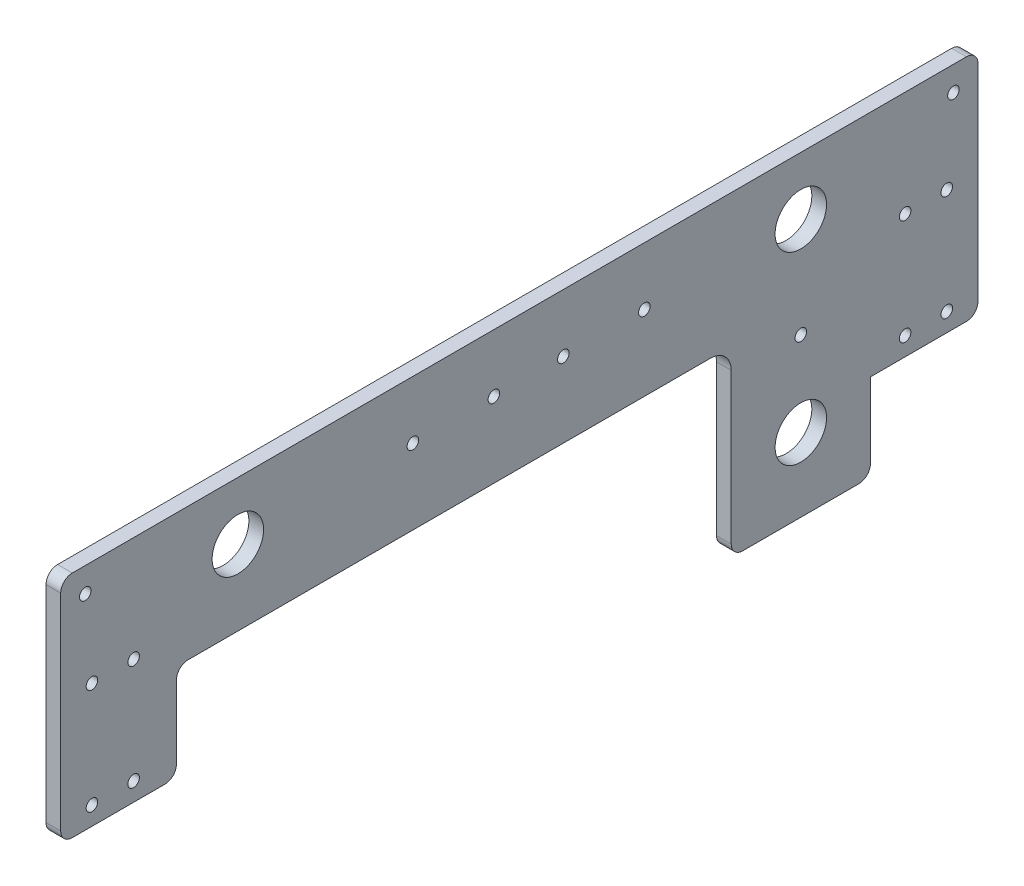
SolidWorks part; units mm, degrees
material "6061-O (SS)"
ref_plane "Alzado" through (0, 0, 0) normal (0, 0, 1) x (1, 0, 0)
ref_plane "Planta" through (0, 0, 0) normal (0, 1, 0) x (1, 0, 0)
ref_plane "Vista lateral" through (0, 0, 0) normal (1, 0, 0) x (0, 0, -1)
sketch "Croquis1" plane through (0, 0, 0) normal (1, 0, 0) x (0, 0, -1)
  line L4 (-30.06, -68.26) -> (-30.06, 1.76)
  line L5 (0, 43.26) -> (0, -68.26) construction
  line L6 (0, 43.26) -> (-243.18, 43.26) construction
  line L7 (30.06, 68.26) -> (-319.71, 68.26) construction
  line L9 (30.06, 10.76) -> (-319.71, 10.76) construction
  line L12 (21.06, 68.26) -> (-319.71, 68.26)
  line L14 (-243.18, 43.26) -> (-243.18, 28.26) construction
  line L15 (-243.18, 28.26) -> (-308.18, 28.26) construction
  line L16 (-30.06, -68.26) -> (30.06, -68.26) construction
  line L24 (-30.06, -68.26) -> (30.06, -68.26)
  line L27 (-319.71, 68.26) -> (-319.71, 10.76)
  line L28 (-319.71, 10.76) -> (-319.71, -30.77)
  line L29 (-319.71, -30.77) -> (-269.71, -30.77)
  line L30 (-39.06, 10.76) -> (-269.71, 10.76)
  line L31 (-269.71, 10.76) -> (-269.71, -30.77)
  line L32 (-269.71, -30.77) -> (30.06, -30.77) construction
  line L33 (30.06, -68.26) -> (30.06, -30.77)
  line L34 (76.54, 68.26) -> (76.54, -30.77)
  line L35 (21.06, 68.26) -> (76.54, 68.26)
  line L36 (30.06, -30.77) -> (76.54, -30.77)
  line L37 (-319.71, 35.76) -> (76.54, 35.76) construction
  line L38 (-121.585, 35.76) -> (-121.585, 143.8043) construction
  circle A0 centre (0, 43.26) radius 11.115
  circle A1 centre (0, -36.51) radius 11.115
  circle A2 centre (-243.18, 43.26) radius 11.115
  circle A3 centre (0, 0) radius 2.5
  circle A4 centre (-67.59, 43.26) radius 2.5
  circle A5 centre (-167.59, 43.26) radius 2.5
  arc A9 (-30.06, 1.76) -> (-39.06, 10.76) centre (-39.06, 1.76) ccw
  circle A11 centre (-132.59, 43.26) radius 2.5
  circle A12 centre (-102.59, 43.26) radius 2.5
  point P0 (0, 0)
  point P30 (-319.71, 35.76)
  point P36 (-30.06, 10.76)
  point P42 (-276.59, 68.26)
  dimension "D8" = 35
  dimension "D9" = 79.77
  dimension "D11" = 22.23
  dimension "D12" = 5
  dimension "D15" = 15
  dimension "D17" = 5
  dimension "D19" = 35
  dimension "D7" = 5
  dimension "D6" = 30.06
  dimension "D1" = 136.52
  dimension "D2" = 60.12
  dimension "D3" = 57.5
  dimension "D4" = 46.48
  dimension "D5" = 25
  dimension "D10" = 243.18
  dimension "D16" = 65
  dimension "D18" = 41.53
  dimension "D20" = 50
extrude "Saliente-Extruir1" add sketch "Croquis1" along normal blind 6.35
sketch "Croquis3" plane through (6.35, 0, 0) normal (1, 0, 0) x (0, 0, -1)
  line L0 (-279.71, -22.77) -> (-319.71, -22.77) construction
  line L1 (-319.71, -30.77) -> (-279.71, -30.77) construction
  line L2 (-319.71, -30.77) -> (-319.71, -14.77) construction
  line L3 (-319.71, -14.77) -> (-279.71, -14.77) construction
  line L4 (-279.71, -30.77) -> (-279.71, -14.77) construction
  line L5 (-319.71, 68.26) -> (-319.71, -30.77) construction
  line L6 (-319.71, 30.78) -> (-279.71, 30.78) construction
  line L7 (-319.71, 30.78) -> (-319.71, 14.78) construction
  line L8 (-319.71, 14.78) -> (-279.71, 14.78) construction
  line L9 (-279.71, 30.78) -> (-279.71, 14.78) construction
  line L10 (-279.71, 22.78) -> (-319.71, 22.78) construction
  line L11 (-319.71, 22.78) -> (-319.71, -22.77) construction
  line L12 (-319.71, 0.005) -> (-279.71, 0.005) construction
  line L13 (-319.71, 14.78) -> (76.54, 14.78) construction
  line L14 (76.54, -30.77) -> (76.54, 68.26) construction
  line L15 (-121.585, 14.78) -> (-121.585, 68.26) construction
  line L16 (76.54, 68.26) -> (-319.71, 68.26) construction
  line L17 (-319.71, 68.26) -> (-309.1034, 57.6534) construction
  circle A0 centre (-288.21, -22.77) radius 2.5
  circle A1 centre (-306.21, -22.77) radius 2.5
  circle A2 centre (-306.21, 22.78) radius 2.5
  circle A3 centre (-288.21, 22.78) radius 2.5
  circle A4 centre (45.04, -22.77) radius 2.5
  circle A5 centre (63.04, -22.77) radius 2.5
  circle A6 centre (45.04, 22.78) radius 2.5
  circle A7 centre (63.04, 22.78) radius 2.5
  circle A8 centre (-309.1034, 57.6534) radius 2.5
  circle A9 centre (65.9334, 57.6534) radius 2.5
  dimension "D3" = 5
  dimension "D4" = 8.5
  dimension "D5" = 18
  dimension "D10" = 5
  dimension "D1" = 40
  dimension "D2" = 16
  dimension "D6" = 16
  dimension "D7" = 40
  dimension "D8" = 61.55
  dimension "D9" = 15
extrude "Cortar-Extruir1" cut sketch "Croquis3" against normal blind 10
fillet "Redondeo1" radius 5 8 edges at (3.175, 68.26, -76.54) (3.175, -30.77, -76.54) (3.175, -68.26, -30.06) (3.175, -68.26, 30.06) (3.175, 10.76, 269.71) (3.175, -30.77, 269.71) (3.175, -30.77, 319.71) (3.175, 68.26, 319.71)
